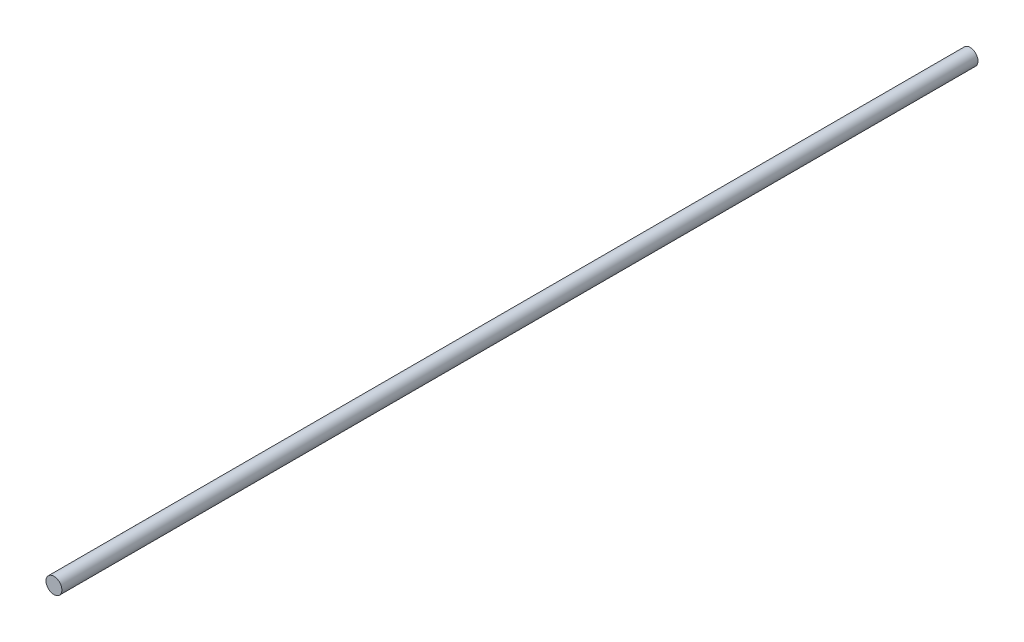
SolidWorks part; units mm, degrees
ref_plane "Front Plane" through (0, 0, 0) normal (0, 0, 1) x (1, 0, 0)
ref_plane "Top Plane" through (0, 0, 0) normal (0, 1, 0) x (1, 0, 0)
ref_plane "Right Plane" through (0, 0, 0) normal (1, 0, 0) x (0, 0, -1)
sketch "Sketch1" plane through (0, 0, 0) normal (0, 0, 1) x (1, 0, 0)
  circle A0 centre (0, 0) radius 5
  dimension "D1" = 10
extrude "Boss-Extrude1" add sketch "Sketch1" along normal blind 576.6
